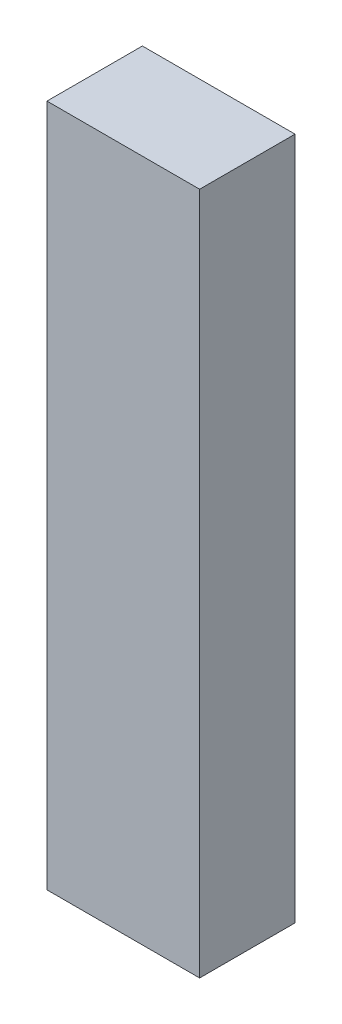
SolidWorks part; units mm, degrees
ref_plane "Front Plane" through (0, 0, 0) normal (0, 0, 1) x (1, 0, 0)
ref_plane "Top Plane" through (0, 0, 0) normal (0, 1, 0) x (1, 0, 0)
ref_plane "Right Plane" through (0, 0, 0) normal (1, 0, 0) x (0, 0, -1)
other "Configuration Table"
sketch "Sketch1" plane through (0, 0, 0) normal (0, 0, 1) x (1, 0, 0)
  line L1 (1298, 1469) -> (1338, 1469)
  line L2 (1298, 1469) -> (1298, 1648)
  line L3 (1298, 1648) -> (1338, 1648)
  line L4 (1338, 1469) -> (1338, 1648)
extrude "DET_kablo_kanali_dilimi_40x25_1" add sketch "Sketch1" against normal blind 25 from offset 765 separate body
